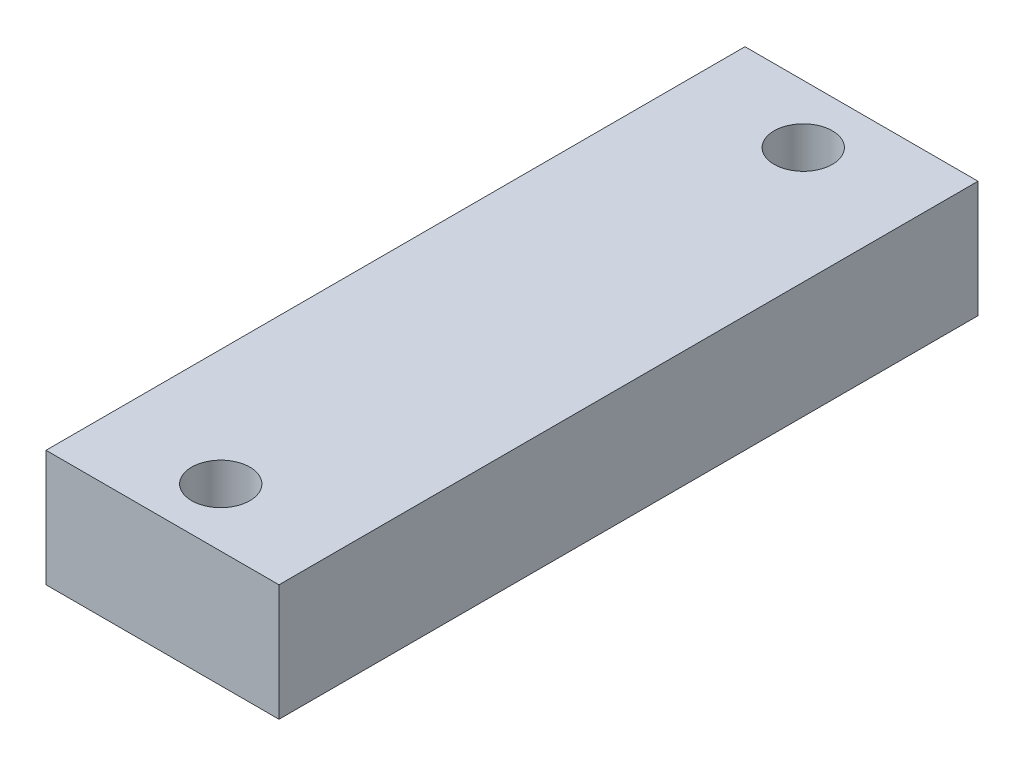
SolidWorks part; units mm, degrees
ref_plane "Front" through (0, 0, 0) normal (0, 0, 1) x (1, 0, 0)
ref_plane "Top" through (0, 0, 0) normal (0, 1, 0) x (1, 0, 0)
ref_plane "Right" through (0, 0, 0) normal (1, 0, 0) x (0, 0, -1)
sketch "Sketch1" plane through (0, 0, 0) normal (0, 1, 0) x (1, 0, 0)
  line L1 (0, 0) -> (12.7, 0)
  line L2 (0, 0) -> (0, 38.1)
  line L3 (0, 38.1) -> (12.7, 38.1)
  line L4 (12.7, 0) -> (12.7, 38.1)
  circle A0 centre (6.35, 34.925) radius 1.5875
  circle A1 centre (6.35, 3.175) radius 1.5875
  point P9 (6.35, 38.1)
  dimension "D3" = 31.75
  dimension "D5" = 3.175
  dimension "D1" = 12.7
  dimension "D2" = 38.1
  dimension "D4" = 3.175
extrude "Boss-Extrude1" add sketch "Sketch1" along normal blind 6.35
